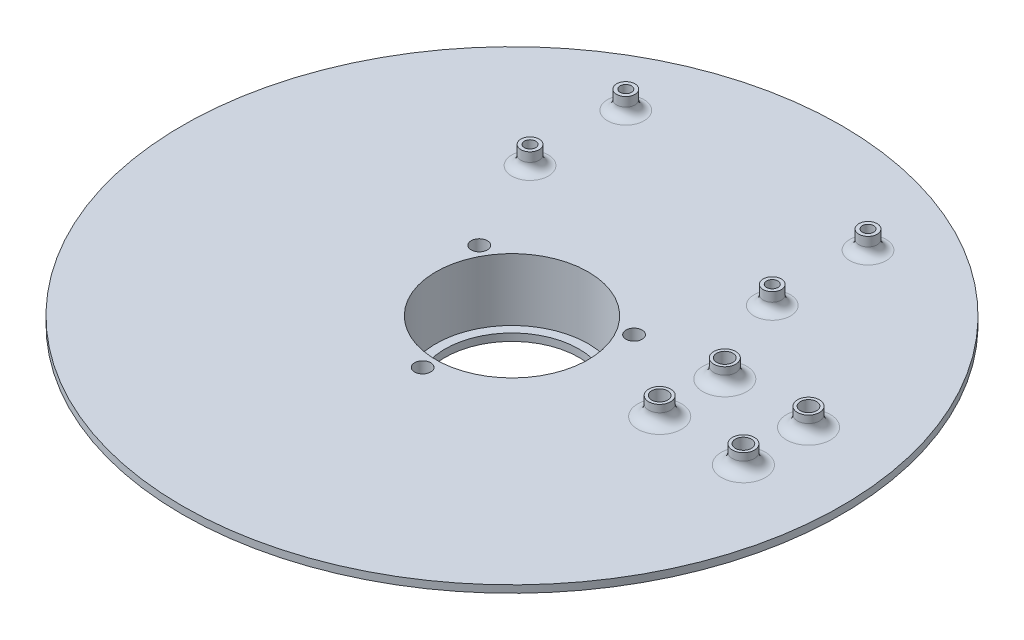
SolidWorks part; units mm, degrees
ref_plane "Front Plane" through (0, 0, 0) normal (0, 0, 1) x (1, 0, 0)
ref_plane "Top Plane" through (0, 0, 0) normal (0, 1, 0) x (1, 0, 0)
ref_plane "Right Plane" through (0, 0, 0) normal (1, 0, 0) x (0, 0, -1)
sketch "Base Plate Outline" plane through (0, 0, 0) normal (0, 1, 0) x (1, 0, 0)
  circle A0 centre (0, 0) radius 90
  dimension "D1" = 180
extrude "Boss-Extrude1" add sketch "Base Plate Outline" along normal blind 2 contours A0
sketch "Sketch3" plane through (0, 0, 0) normal (0, -1, 0) x (1, 0, 0)
  circle A0 centre (0, 0) radius 28
  dimension "D1" = 56
extrude "Boss-Extrude2" add sketch "Sketch3" along normal blind 17
sketch "Sketch4" plane through (0, -17, 0) normal (0, -1, 0) x (1, 0, 0)
  circle A0 centre (0, 0) radius 20.8
  dimension "D1" = 41.6
extrude "Cut-Extrude1" cut sketch "Sketch4" against normal through all
sketch "Sketch7" plane through (0, -17, 0) normal (0, -1, 0) x (1, 0, 0)
  circle A0 centre (0, 0) radius 28 construction
  circle A1 centre (0, 0) radius 28
extrude "Boss-Extrude3" add sketch "Sketch7" against normal blind 2
sketch "Sketch8" plane through (0, -17, 0) normal (0, -1, 0) x (1, 0, 0)
  circle A0 centre (0, 0) radius 18.3
  dimension "D1" = 36.6
extrude "Cut-Extrude3" cut sketch "Sketch8" against normal blind 2
sketch "Sketch13" plane through (0, 2, 0) normal (0, 1, 0) x (1, 0, 0)
  line L1 (0, -20.8) -> (0, -28) construction
  circle A0 centre (0, -24.4) radius 2.2
  circle A1 centre (0, 0) radius 28 construction
  circle A2 centre (0, 0) radius 20.8 construction
  circle A3 centre (-21.131, 12.2) radius 2.2
  circle A4 centre (21.131, 12.2) radius 2.2
  point P16 (0, 0)
  dimension "D1" = 4.4
  dimension "D3" = 56
  dimension "D2" = 3
  dimension "D4" = 12.2
  dimension "D5" = 21.131
extrude "Cut-Extrude6" cut sketch "Sketch13" against normal blind 6
sketch "Sketch9" plane through (0, 2, 0) normal (0, 1, 0) x (1, 0, 0)
  line L0 (0, 0) -> (0, 90) construction
  circle A0 centre (-33.075, 38) radius 2.5
  circle A1 centre (0, 0) radius 90 construction
  circle A2 centre (-33.075, 64.15) radius 2.5
  circle A3 centre (33.075, 64.15) radius 2.5
  circle A4 centre (33.075, 38) radius 2.5
  dimension "D1" = 5
  dimension "D2" = 33.075
  dimension "D3" = 5
  dimension "D4" = 26.15
  dimension "D5" = 38
  dimension "D6" = 33.075
extrude "Boss-Extrude4" add sketch "Sketch9" along normal blind 5
sketch "Sketch10" plane through (0, 7, 0) normal (0, 1, 0) x (1, 0, 0)
  line L0 (0, 0) -> (0, 90) construction
  circle A0 centre (-33.075, 38) radius 1.55
  circle A1 centre (-33.075, 64.15) radius 1.55
  circle A2 centre (0, 0) radius 90 construction
  circle A3 centre (33.075, 38) radius 1.55
  circle A4 centre (33.075, 64.15) radius 1.55
  dimension "D1" = 3.1
  dimension "D2" = 3.1
extrude "Cut-Extrude4" cut sketch "Sketch10" against normal blind 5
fillet "Fillet1" radius 2.5 4 edges at (-33.075, 2, -61.65) (-33.075, 2, -35.5) (33.075, 2, -66.65) (33.075, 2, -40.5)
sketch "Sketch11" plane through (0, 2, 0) normal (0, 1, 0) x (1, 0, 0)
  line L0 (0, 0) -> (90, 0) construction
  line L1 (55.43, 0) -> (55.43, -12) construction
  circle A0 centre (0, 0) radius 90 construction
  circle A1 centre (44, -3.667) radius 3
  circle A2 centre (44, 14.113) radius 3
  circle A3 centre (66.86, -3.667) radius 3
  circle A4 centre (66.86, 14.113) radius 3
  dimension "D1" = 6
  dimension "D3" = 6
  dimension "D2" = 3.667
  dimension "D4" = 14.113
  dimension "D5" = 11.43
  dimension "D6" = 12
  dimension "D7" = 44
  dimension "D8" = 44
extrude "Boss-Extrude5" add sketch "Sketch11" along normal blind 5
sketch "Sketch12" plane through (0, 7, 0) normal (0, 1, 0) x (1, 0, 0)
  circle A0 centre (44, -3.667) radius 2.2
  circle A1 centre (44, 14.113) radius 2.2
  circle A2 centre (66.86, 14.113) radius 2.2
  circle A3 centre (66.86, -3.667) radius 2.2
  dimension "D1" = 4.4
  dimension "D2" = 4.4
  dimension "D3" = 4.4
  dimension "D4" = 4.4
extrude "Cut-Extrude5" cut sketch "Sketch12" against normal blind 5
fillet "Fillet2" radius 3 4 edges at (66.86, 2, 0.667) (66.86, 2, -17.113) (44, 2, -11.113) (44, 2, 6.667)
